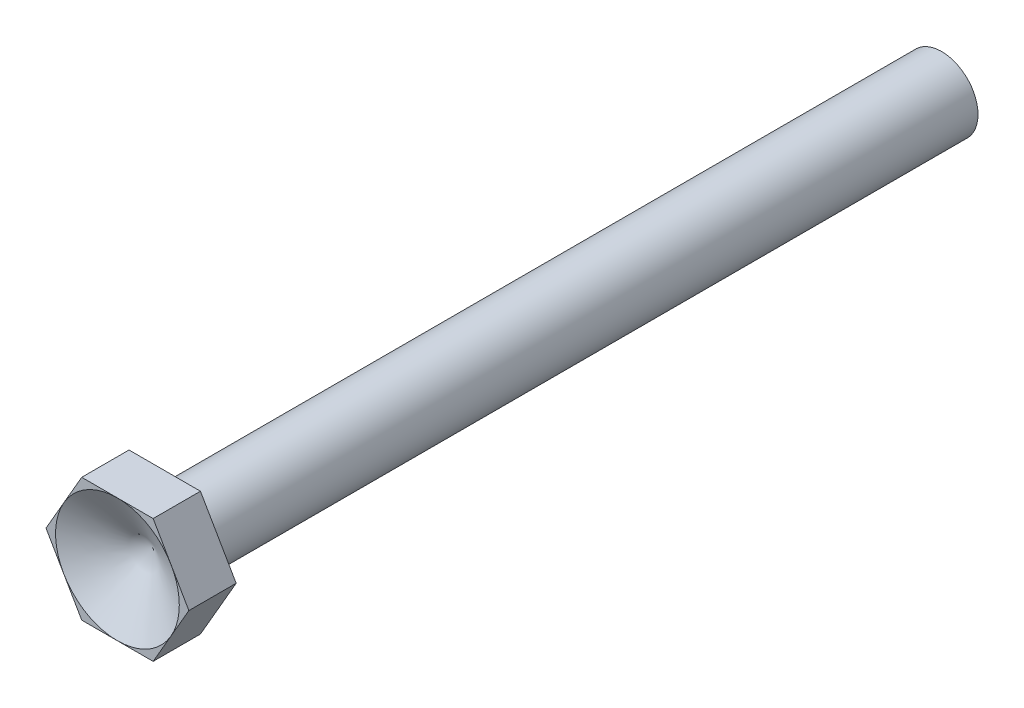
SolidWorks part; units mm, degrees
ref_plane "Front Plane" through (0, 0, 0) normal (0, 0, 1) x (1, 0, 0)
ref_plane "Top Plane" through (0, 0, 0) normal (0, 1, 0) x (1, 0, 0)
ref_plane "Right Plane" through (0, 0, 0) normal (1, 0, 0) x (0, 0, -1)
sketch "Sketch1" plane through (0, 0, 0) normal (0, 0, 1) x (1, 0, 0)
  circle A0 centre (0, 0) radius 10
  dimension "D1" = 20
extrude "Boss-Extrude1" add sketch "Sketch1" along normal mid plane 220
cosmetic thread "Cosmetic Thread1" parameters "D1"=15, "D2"=17.252
sketch "Sketch3" plane through (0, 0, 110) normal (0, 0, 1) x (1, 0, 0)
  line L1 (19.6299, 0) -> (9.815, 17)
  line L2 (9.815, 17) -> (-9.815, 17)
  line L3 (-9.815, 17) -> (-19.6299, 0)
  line L4 (-19.6299, 0) -> (-9.815, -17)
  line L5 (-9.815, -17) -> (9.815, -17)
  line L6 (9.815, -17) -> (19.6299, 0)
  circle A0 centre (0, 0) radius 17 construction
  dimension "D1" = 34
extrude "Boss-Extrude2" add sketch "Sketch3" along normal mid plane 13 contours L1 L2 L3 L4 L5 L6
sketch "Sketch6" plane through (0, 0, 116.5) normal (0, 0, 1) x (1, 0, 0)
  line L0 (-9.815, 17) -> (-19.6299, 0) construction
  circle A0 centre (0, 0) radius 17
extrude "Cut-Extrude1" cut sketch "Sketch6" against normal through all draft 60
